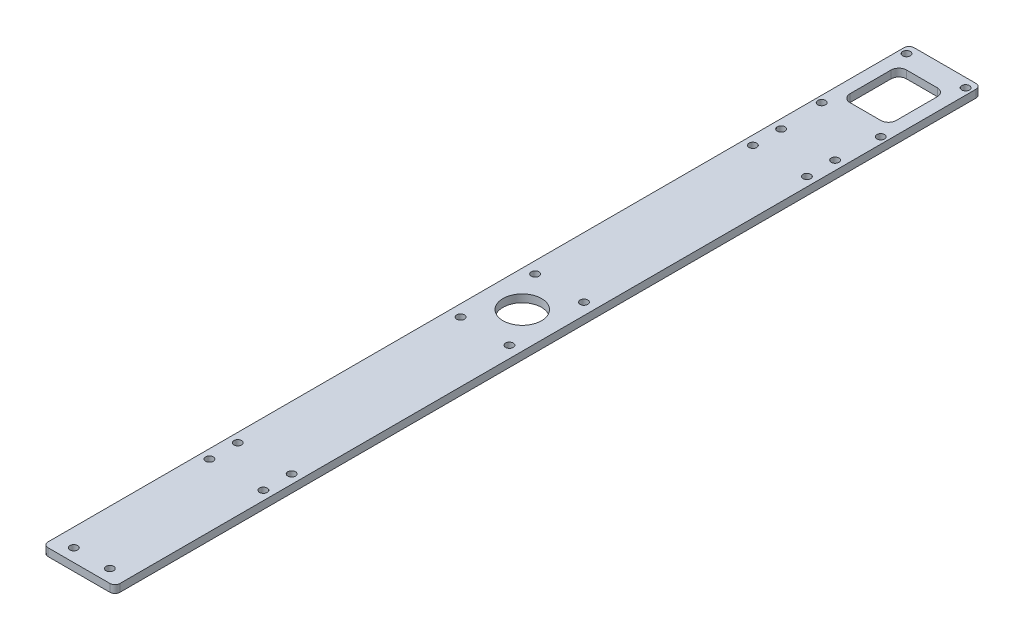
SolidWorks part; units mm, degrees
ref_plane "前视基准面" through (0, 0, 0) normal (0, 0, 1) x (1, 0, 0)
ref_plane "上视基准面" through (0, 0, 0) normal (0, 1, 0) x (1, 0, 0)
ref_plane "右视基准面" through (0, 0, 0) normal (1, 0, 0) x (0, 0, -1)
sketch "草图1" plane through (0, 0, 0) normal (0, 0, 1) x (1, 0, 0)
  line L1 (-14, 1.5) -> (14, 1.5)
  line L2 (-14, 1.5) -> (-14, -1.5)
  line L3 (-14, -1.5) -> (14, -1.5)
  line L4 (14, 1.5) -> (14, -1.5)
  line L5 (-14, 1.5) -> (14, -1.5) construction
  line L6 (-14, -1.5) -> (14, 1.5) construction
  point P0 (0, 0)
  dimension "D1" = 3
  dimension "D2" = 28
extrude "凸台-拉伸1" add sketch "草图1" along normal blind 337
sketch "草图2" plane through (0, -1.5, 0) normal (0, -1, 0) x (1, 0, 0)
  line L0 (-14, 0) -> (14, 0) construction
  line L1 (-14, 337) -> (-14, 0) construction
  line L3 (-9.5, 179) -> (9.5, 179) construction
  line L4 (-9.5, 179) -> (-9.5, 150) construction
  line L5 (-9.5, 150) -> (9.5, 150) construction
  line L6 (9.5, 179) -> (9.5, 150) construction
  line L7 (-9.5, 179) -> (9.5, 150) construction
  line L8 (-9.5, 150) -> (9.5, 179) construction
  circle A0 centre (0, 164.5) radius 7.5
  circle A1 centre (-9.5, 179) radius 1.5
  circle A2 centre (9.5, 179) radius 1.5
  circle A3 centre (9.5, 150) radius 1.5
  circle A4 centre (-9.5, 150) radius 1.5
  dimension "D1" = 15
  dimension "D2" = 164.5
  dimension "D3" = 14
  dimension "D6" = 3
  dimension "D7" = 3
  dimension "D8" = 3
  dimension "D9" = 3
  dimension "D4" = 29
  dimension "D5" = 19
extrude "切除-拉伸1" cut sketch "草图2" against normal blind 400
sketch "草图3" plane through (0, 1.5, 0) normal (0, 1, 0) x (1, 0, 0)
  line L0 (14, 0) -> (-14, 0) construction
  line L1 (11.5, -36.5) -> (-11.5, -36.5) construction
  line L2 (11.5, -36.5) -> (11.5, -3.5) construction
  line L3 (11.5, -3.5) -> (-11.5, -3.5) construction
  line L4 (-11.5, -36.5) -> (-11.5, -3.5) construction
  line L5 (-14, -337) -> (-14, 0) construction
  line L6 (0, 0) -> (0, -9) construction
  line L7 (0, -9) -> (0, -20) construction
  line L13 (-9, -9) -> (9, -9)
  line L14 (-9, -9) -> (-9, -31)
  line L15 (-9, -31) -> (9, -31)
  line L16 (9, -9) -> (9, -31)
  line L17 (-9, -9) -> (9, -31) construction
  line L18 (-9, -31) -> (9, -9) construction
  circle A0 centre (11.5, -3.5) radius 1.5
  circle A1 centre (-11.5, -3.5) radius 1.5
  circle A2 centre (-11.5, -36.5) radius 1.5
  circle A3 centre (11.5, -36.5) radius 1.5
  point P0 (0, -20)
  point P12 (0, -20)
  dimension "D4" = 3
  dimension "D5" = 3
  dimension "D6" = 3
  dimension "D7" = 3
  dimension "D8" = 2.5
  dimension "D10" = 11
  dimension "D1" = 33
  dimension "D2" = 23
  dimension "D3" = 3.5
  dimension "D9" = 9
  dimension "D11" = 22
  dimension "D12" = 18
extrude "切除-拉伸2" cut sketch "草图3" against normal blind 10
sketch "草图4" plane through (0, 1.5, 0) normal (0, 1, 0) x (1, 0, 0)
  line L0 (14, -337) -> (-14, -337) construction
  line L1 (-7, -325) -> (7, -325) construction
  line L2 (-7, -325) -> (-7, -332) construction
  line L3 (-7, -332) -> (7, -332) construction
  line L4 (7, -325) -> (7, -332) construction
  line L5 (-7, -325) -> (7, -332) construction
  line L6 (-7, -332) -> (7, -325) construction
  circle A2 centre (7, -332) radius 1.5
  circle A3 centre (-7, -332) radius 1.5
  point P0 (0, -328.5)
  dimension "D6" = 3
  dimension "D7" = 3
  dimension "D1" = 7
  dimension "D2" = 14
  dimension "D3" = 5
extrude "切除-拉伸3" cut sketch "草图4" against normal blind 10
sketch "草图5" plane through (0, -1.5, 0) normal (0, -1, 0) x (1, 0, 0)
  line L0 (14, 0) -> (-14, 0) construction
  circle A0 centre (-10.5, 264.73) radius 1.5
  circle A1 centre (-10.5, 275.73) radius 1.5
  circle A2 centre (10.5, 275.73) radius 1.5
  circle A3 centre (10.5, 264.73) radius 1.5
  dimension "D1" = 3
  dimension "D2" = 3
  dimension "D3" = 3
  dimension "D4" = 3
  dimension "D9" = 21
  dimension "D5" = 21
  dimension "D6" = 11
  dimension "D7" = 264.73
  dimension "D8" = 11
extrude "切除-拉伸4" cut sketch "草图5" against normal blind 10
fillet "圆角1" radius 2 4 edges at (-14, 0, 0) (-14, 0, 337) (14, 0, 337) (14, 0, 0)
fillet "圆角3" radius 3 4 edges at (9, 0, 9) (-9, 0, 9) (9, 0, 31) (-9, 0, 31)
pattern_linear "阵列(线性)1" count 2 spacing 211.46 along (0, 0, -1) of "切除-拉伸4"
